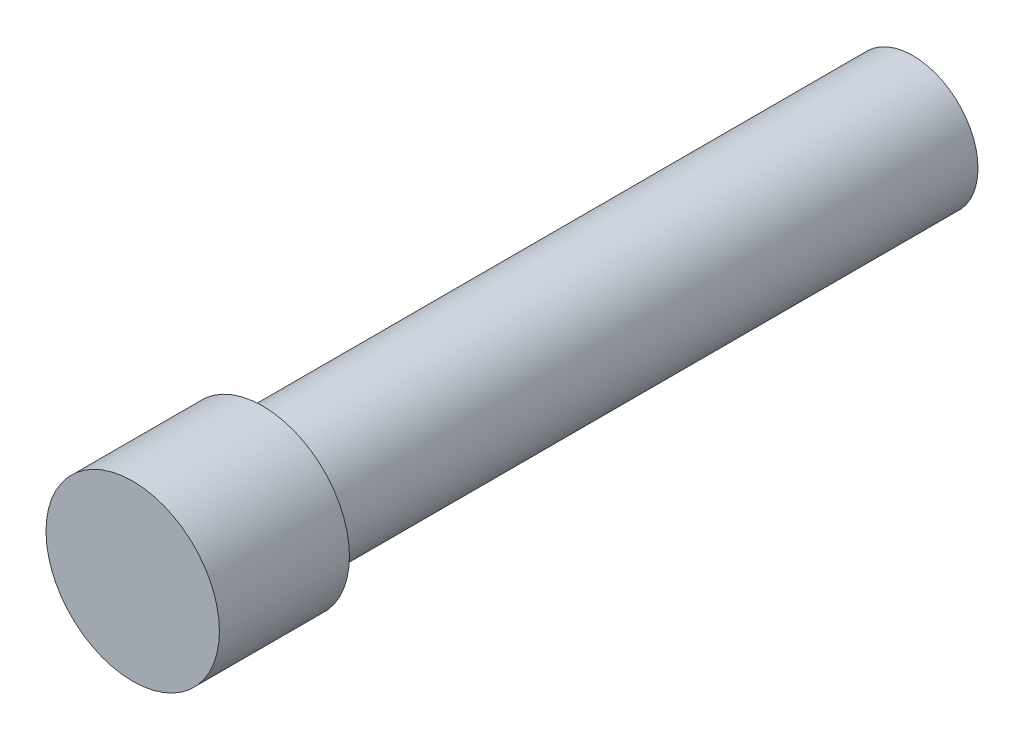
SolidWorks part; units mm, degrees
ref_plane "Front Plane" through (0, 0, 0) normal (0, 0, 1) x (1, 0, 0)
ref_plane "Top Plane" through (0, 0, 0) normal (0, 1, 0) x (1, 0, 0)
ref_plane "Right Plane" through (0, 0, 0) normal (1, 0, 0) x (0, 0, -1)
sketch "Sketch1" plane through (0, 0, 0) normal (0, 0, 1) x (1, 0, 0)
  circle A0 centre (0, 0) radius 1.5
  dimension "D1" = 3
extrude "Boss-Extrude1" add sketch "Sketch1" along normal blind 15
sketch "Sketch3" plane through (0, 0, 15) normal (0, 0, 1) x (1, 0, 0)
  circle A0 centre (0, 0) radius 2
  dimension "D1" = 4
extrude "Boss-Extrude2" add sketch "Sketch3" along normal blind 3
